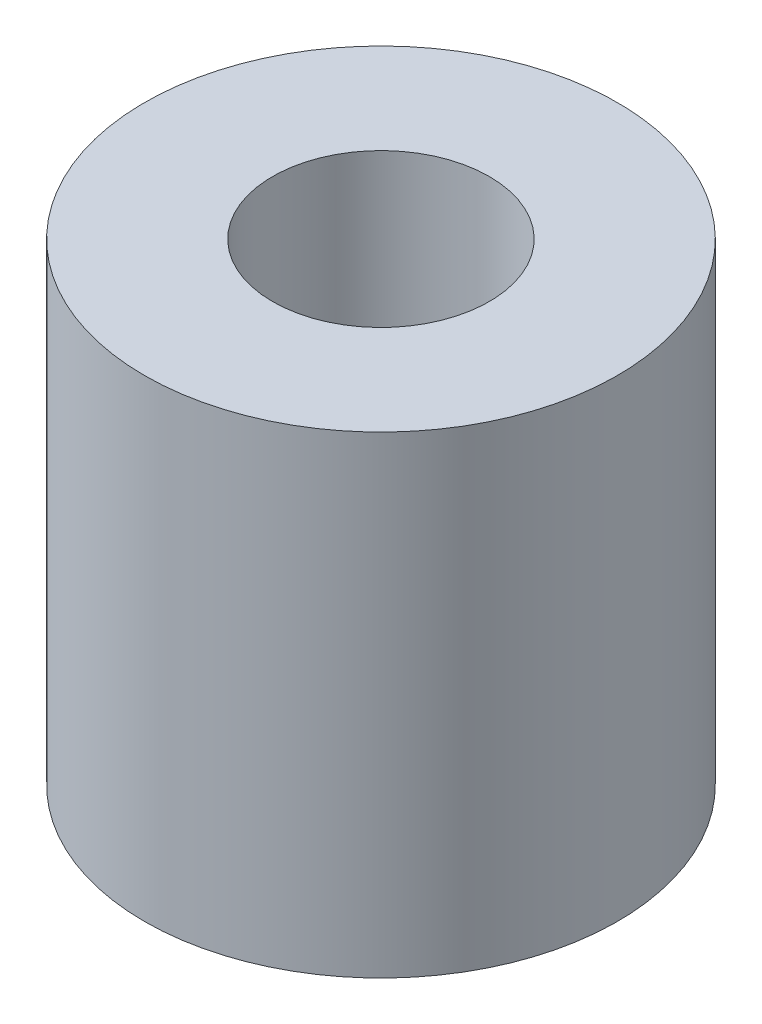
SolidWorks part; units mm, degrees
ref_plane "Front" through (0, 0, 0) normal (0, 0, 1) x (1, 0, 0)
ref_plane "Top" through (0, 0, 0) normal (0, 1, 0) x (1, 0, 0)
ref_plane "Right" through (0, 0, 0) normal (1, 0, 0) x (0, 0, -1)
sketch "Sketch1" plane through (0, 0, 0) normal (0, 1, 0) x (1, 0, 0)
  circle A0 centre (0, 0) radius 3
  circle A1 centre (0, 0) radius 1.375
  dimension "D1" = 6
  dimension "D2" = 2.75
extrude "Boss-Extrude1" add sketch "Sketch1" along normal blind 6
